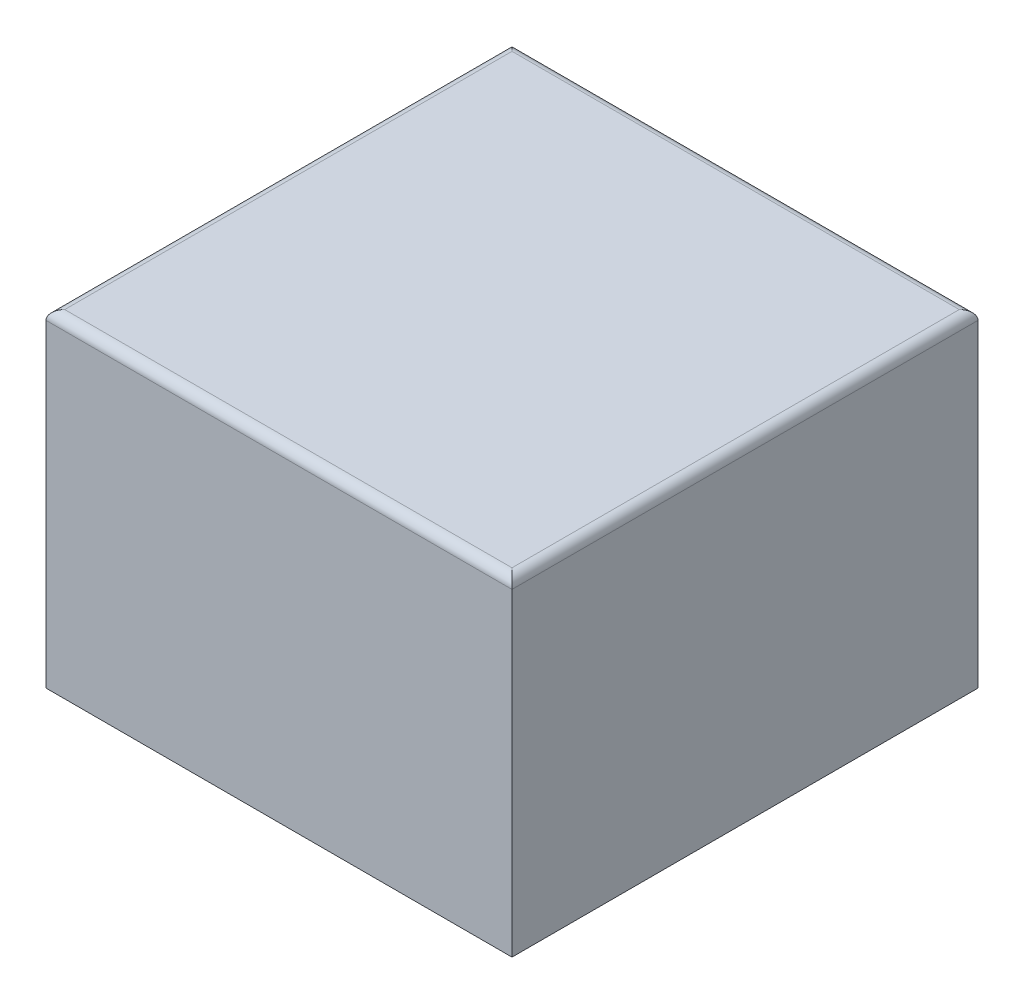
SolidWorks part; units mm, degrees
ref_plane "Front Plane" through (0, 0, 0) normal (0, 0, 1) x (1, 0, 0)
ref_plane "Top Plane" through (0, 0, 0) normal (0, 1, 0) x (1, 0, 0)
ref_plane "Right Plane" through (0, 0, 0) normal (1, 0, 0) x (0, 0, -1)
sketch "Sketch1" plane through (0, 0, 0) normal (0, 1, 0) x (1, 0, 0)
  line L1 (4.975, -4.975) -> (-4.975, -4.975)
  line L2 (4.975, -4.975) -> (4.975, 4.975)
  line L3 (4.975, 4.975) -> (-4.975, 4.975)
  line L4 (-4.975, -4.975) -> (-4.975, 4.975)
  line L5 (4.975, -4.975) -> (-4.975, 4.975) construction
  line L6 (4.975, 4.975) -> (-4.975, -4.975) construction
  point P0 (0, 0)
extrude "Boss-Extrude1" add sketch "Sketch1" along normal blind 7
fillet "Fillet1" radius 0.2 4 edges at (4.975, 7, 0) (0, 7, -4.975) (-4.975, 7, 0) (0, 7, 4.975)
